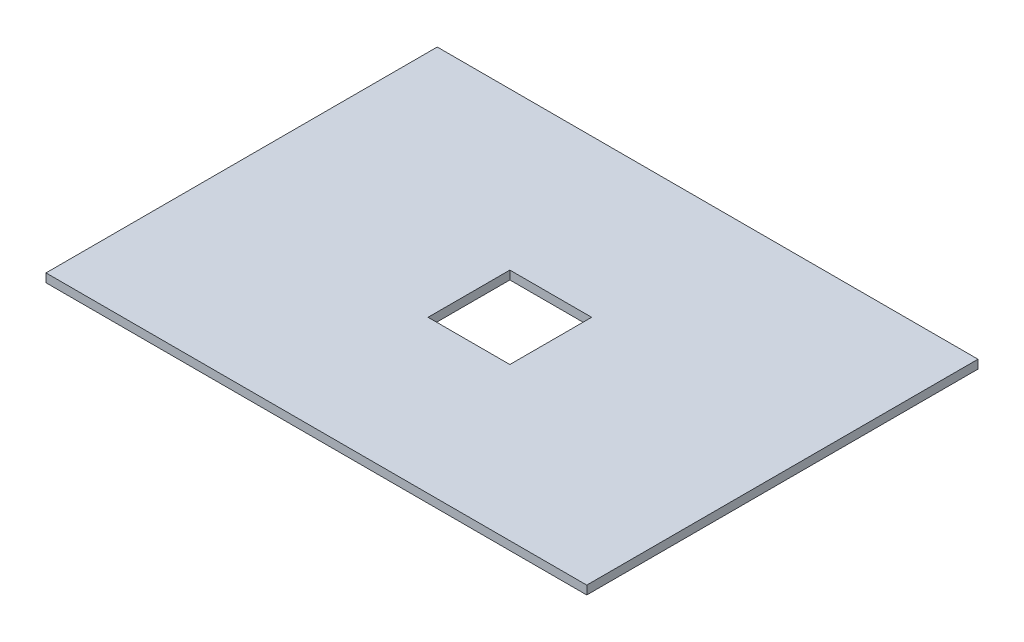
SolidWorks part; units mm, degrees
ref_plane "Front Plane" through (0, 0, 0) normal (0, 0, 1) x (1, 0, 0)
ref_plane "Top Plane" through (0, 0, 0) normal (0, 1, 0) x (1, 0, 0)
ref_plane "Right Plane" through (0, 0, 0) normal (1, 0, 0) x (0, 0, -1)
sketch "Sketch1" plane through (0, 0, 0) normal (0, 1, 0) x (1, 0, 0)
  line L0 (13.7, 289.4) -> (386.3, 289.4)
  line L1 (0, 0) -> (400, 0)
  line L2 (0, 0) -> (0, 289.4)
  line L3 (0, 289.4) -> (6.35, 289.4)
  line L4 (400, 0) -> (400, 289.4)
  line L13 (393.65, 289.4) -> (400, 289.4)
  line L14 (6.35, 289.4) -> (13.7, 289.4)
  line L15 (386.3, 289.4) -> (393.65, 289.4)
  line L17 (169.75, 173.36) -> (230.25, 173.36)
  line L18 (169.75, 173.36) -> (169.75, 112.86)
  line L19 (169.75, 112.86) -> (230.25, 112.86)
  line L20 (230.25, 173.36) -> (230.25, 112.86)
  dimension "D1" = 400
  dimension "D2" = 289.4
  dimension "D3" = 60.5
  dimension "D4" = 60.5
  dimension "D5" = 169.75
  dimension "D6" = 112.86
extrude "Boss-Extrude1" add sketch "Sketch1" along normal blind 6.35
